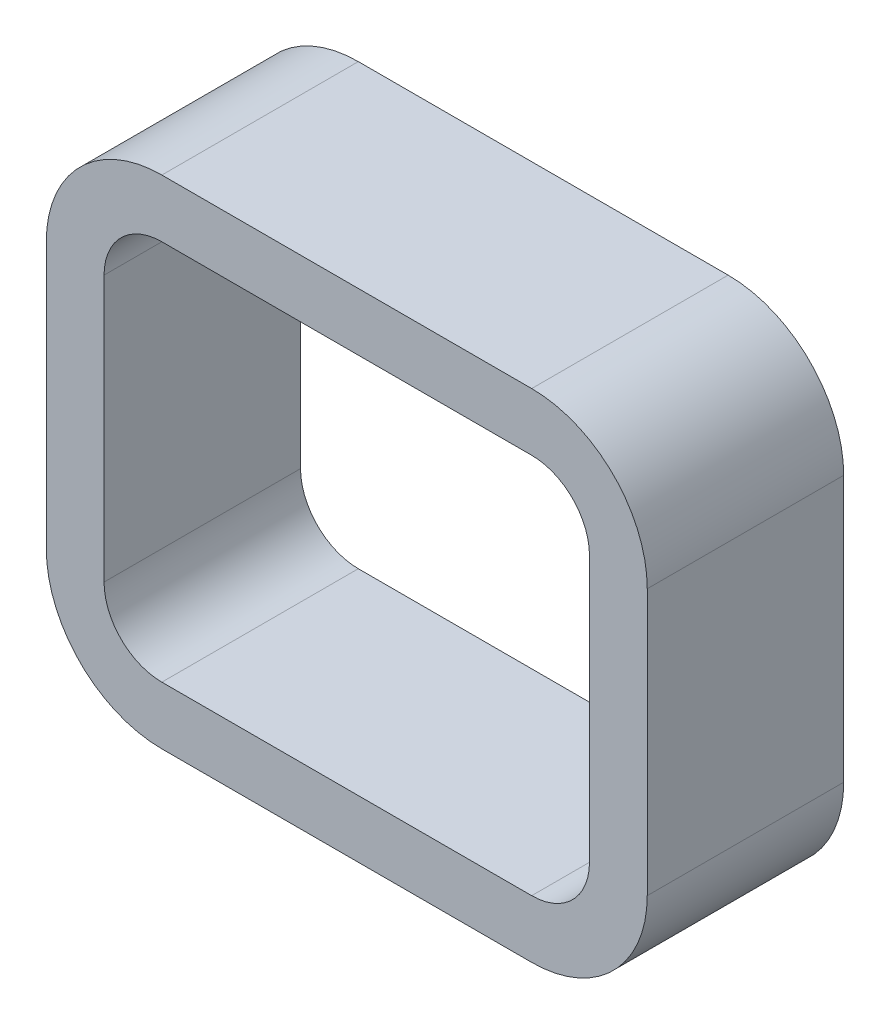
SolidWorks part; units mm, degrees
ref_plane "Front" through (0, 0, 0) normal (0, 0, 1) x (1, 0, 0)
ref_plane "Top" through (0, 0, 0) normal (0, 1, 0) x (1, 0, 0)
ref_plane "Right" through (0, 0, 0) normal (1, 0, 0) x (0, 0, -1)
sketch "Sketch1" plane through (0, 0, 0) normal (0, 0, 1) x (1, 0, 0)
  line L1 (-1.2077, 20.8632) -> (-33.2077, 20.8632)
  line L2 (3.7923, 15.8632) -> (3.7923, -7.1368)
  line L3 (-1.2077, -12.1368) -> (-33.2077, -12.1368)
  line L4 (-38.2077, 15.8632) -> (-38.2077, -7.1368)
  line L5 (3.7923, 20.8632) -> (-38.2077, -12.1368) construction
  line L6 (3.7923, -12.1368) -> (-38.2077, 20.8632) construction
  arc A0 (-33.2077, 20.8632) -> (-38.2077, 15.8632) centre (-33.2077, 15.8632) ccw
  arc A1 (3.7923, -7.1368) -> (-1.2077, -12.1368) centre (-1.2077, -7.1368) cw
  arc A2 (-1.2077, 20.8632) -> (3.7923, 15.8632) centre (-1.2077, 15.8632) cw
  arc A3 (-33.2077, -12.1368) -> (-38.2077, -7.1368) centre (-33.2077, -7.1368) cw
  point P0 (-17.2077, 4.3632)
  dimension "D3" = 5
  dimension "D4" = 5
  dimension "D5" = 5
  dimension "D6" = 5
  dimension "D1" = 42
  dimension "D2" = 33
extrude "Extrude-Thin3" add sketch "Sketch1" along normal blind 17 thin
sketch "Sketch2" plane through (0, 0, 0) normal (0, 0, 1) x (1, 0, 0)
  line L1 (-1.0648, 25.9755) -> (-33.9599, 25.9755)
  line L2 (8.9352, 15.9755) -> (8.9352, -7.0245)
  line L3 (-1.0648, -17.0245) -> (-33.9599, -17.0245)
  line L4 (-43.9599, 15.9755) -> (-43.9599, -7.0245)
  line L5 (8.9352, 25.9755) -> (-43.9599, -17.0245) construction
  line L6 (8.9352, -17.0245) -> (-43.9599, 25.9755) construction
  arc A0 (-1.0648, 25.9755) -> (8.9352, 15.9755) centre (-1.0648, 15.9755) cw
  arc A1 (-1.0648, -17.0245) -> (8.9352, -7.0245) centre (-1.0648, -7.0245) ccw
  arc A2 (-43.9599, 15.9755) -> (-33.9599, 25.9755) centre (-33.9599, 15.9755) cw
  arc A3 (-43.9599, -7.0245) -> (-33.9599, -17.0245) centre (-33.9599, -7.0245) ccw
  point P0 (-17.5124, 4.4755)
  dimension "D1" = 10
  dimension "D2" = 10
  dimension "D3" = 10
  dimension "D4" = 10
  dimension "D5" = 32.8951
  dimension "D6" = 23
